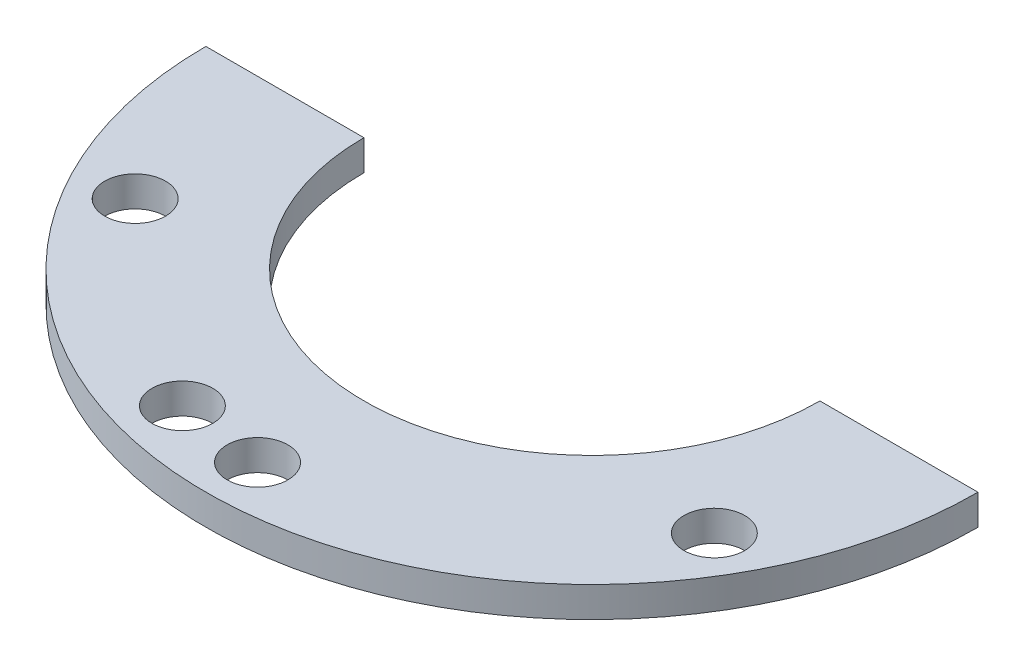
SolidWorks part; units mm, degrees
material "ABS"
ref_plane "Front Plane" through (0, 0, 0) normal (0, 0, 1) x (1, 0, 0)
ref_plane "Top Plane" through (0, 0, 0) normal (0, 1, 0) x (1, 0, 0)
ref_plane "Right Plane" through (0, 0, 0) normal (1, 0, 0) x (0, 0, -1)
sketch "Sketch1" plane through (0, 0, 0) normal (0, 1, 0) x (1, 0, 0)
  circle A0 centre (0, 0) radius 12.7
  dimension "D1" = 25.4
extrude "Boss-Extrude1" add sketch "Sketch1" along normal blind 1
sketch "Sketch19" plane through (0, 1, 0) normal (0, 1, 0) x (1, 0, 0)
  circle A0 centre (0, 11) radius 1
  circle A1 centre (9.5263, 5.5) radius 1
  circle A2 centre (9.5263, -5.5) radius 1
  circle A3 centre (0, -11) radius 1
  circle A4 centre (-9.5263, -5.5) radius 1
  circle A5 centre (-9.5263, 5.5) radius 1
  point P13 (0, 0)
  dimension "D1" = 2
  dimension "D2" = 11
  dimension "D3" = 6
extrude "Cut-Extrude1" cut sketch "Sketch19" against normal through all both and the other way through all
sketch "Sketch20" plane through (0, 1, 0) normal (0, 1, 0) x (1, 0, 0)
  circle A0 centre (0, 0) radius 7.5
  dimension "D1" = 15
extrude "Cut-Extrude2" cut sketch "Sketch20" against normal through all both and the other way through all
sketch "Sketch21" plane through (0, 0, 0) normal (0, 0, 1) x (1, 0, 0)
  line L1 (-36.7533, 32.3113) -> (29.1209, 32.3113)
  line L2 (-36.7533, 32.3113) -> (-36.7533, -19.668)
  line L3 (-36.7533, -19.668) -> (29.1209, -19.668)
  line L4 (29.1209, 32.3113) -> (29.1209, -19.668)
extrude "Cut-Extrude3" cut sketch "Sketch21" against normal through all
sketch "Sketch22" plane through (0, 1, 0) normal (0, 1, 0) x (1, 0, 0)
  line L0 (9.5263, -5.5) -> (0, -11)
  line L1 (0, 0) -> (4.7631, -8.25) construction
  line L2 (4.7631, -8.25) -> (0, 0) construction
  line L3 (0, 0) -> (-4.2868, -15.9987) construction
  circle A0 centre (-2.847, -10.6252) radius 1
  dimension "D1" = 2
  dimension "D2" = 11
  dimension "D3" = 45
extrude "Cut-Extrude4" cut sketch "Sketch22" against normal through all both and the other way through all contours A0
